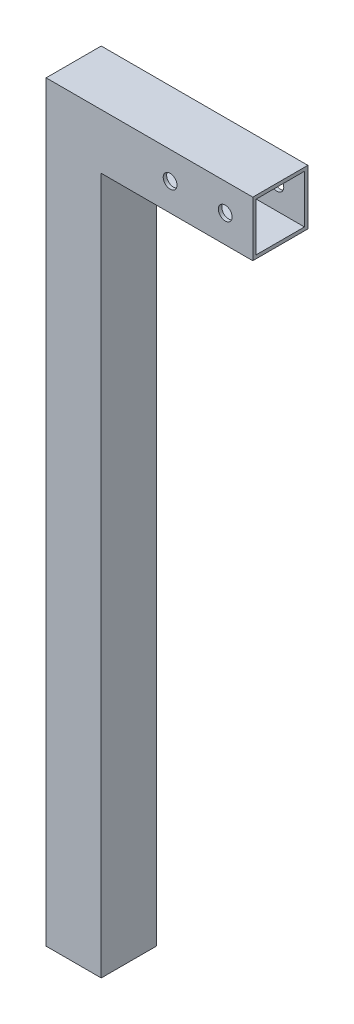
SolidWorks part; units mm, degrees
ref_plane "Front Plane" through (0, 0, 0) normal (0, 0, 1) x (1, 0, 0)
ref_plane "Top Plane" through (0, 0, 0) normal (0, 1, 0) x (1, 0, 0)
ref_plane "Right Plane" through (0, 0, 0) normal (1, 0, 0) x (0, 0, -1)
sketch "Sketch1" plane through (0, 0, 0) normal (0, 1, 0) x (1, 0, 0)
  line L1 (-12.7, 12.7) -> (12.7, 12.7)
  line L2 (-12.7, 12.7) -> (-12.7, -12.7)
  line L3 (-12.7, -12.7) -> (12.7, -12.7)
  line L4 (12.7, 12.7) -> (12.7, -12.7)
  line L5 (-12.7, 12.7) -> (12.7, -12.7) construction
  line L6 (-12.7, -12.7) -> (12.7, 12.7) construction
  line L7 (11.1125, -11.1125) -> (-11.1125, -11.1125)
  line L8 (11.1125, -11.1125) -> (11.1125, 11.1125)
  line L9 (11.1125, 11.1125) -> (-11.1125, 11.1125)
  line L10 (-11.1125, -11.1125) -> (-11.1125, 11.1125)
  line L11 (11.1125, -11.1125) -> (-11.1125, 11.1125) construction
  line L12 (11.1125, 11.1125) -> (-11.1125, -11.1125) construction
  point P0 (0, 0)
  point P6 (0, 0)
  dimension "D1" = 25.4
  dimension "D2" = 1.5875
extrude "Boss-Extrude1" add sketch "Sketch1" along normal blind 321.23
other "1in Square tube<1>"
sketch "Sketch2" plane through (-12.7, 0, 0) normal (-1, 0, 0) x (0, 0, 1)
  line L0 (0, 322.8175) -> (0, 321.23) construction
  line L1 (-12.7, 321.23) -> (12.7, 321.23)
  line L2 (-12.7, 321.23) -> (-12.7, 346.63)
  line L3 (-12.7, 346.63) -> (12.7, 346.63)
  line L4 (12.7, 321.23) -> (12.7, 346.63)
  line L5 (-11.1125, 322.8175) -> (11.1125, 322.8175)
  line L6 (-11.1125, 322.8175) -> (-11.1125, 345.0425)
  line L7 (-11.1125, 345.0425) -> (11.1125, 345.0425)
  line L8 (11.1125, 322.8175) -> (11.1125, 345.0425)
  line L9 (11.1125, 333.93) -> (12.7, 333.93) construction
  dimension "D1" = 1.5875
extrude "Boss-Extrude2" add sketch "Sketch2" against normal blind 95.25
sketch "Sketch3" plane through (0, 0, 12.7) normal (0, 0, 1) x (1, 0, 0)
  line L0 (82.55, 321.23) -> (82.55, 346.63) construction
  line L1 (82.55, 345.0425) -> (82.55, 322.8175) construction
  circle A0 centre (44.45, 333.93) radius 3.175
  circle A1 centre (69.85, 333.93) radius 3.175
  point P6 (82.55, 333.93)
  point P7 (82.55, 333.93)
  dimension "D3" = 6.35
  dimension "D1" = 25.4
  dimension "D2" = 12.7
extrude "Cut-Extrude1" cut sketch "Sketch3" against normal through all
